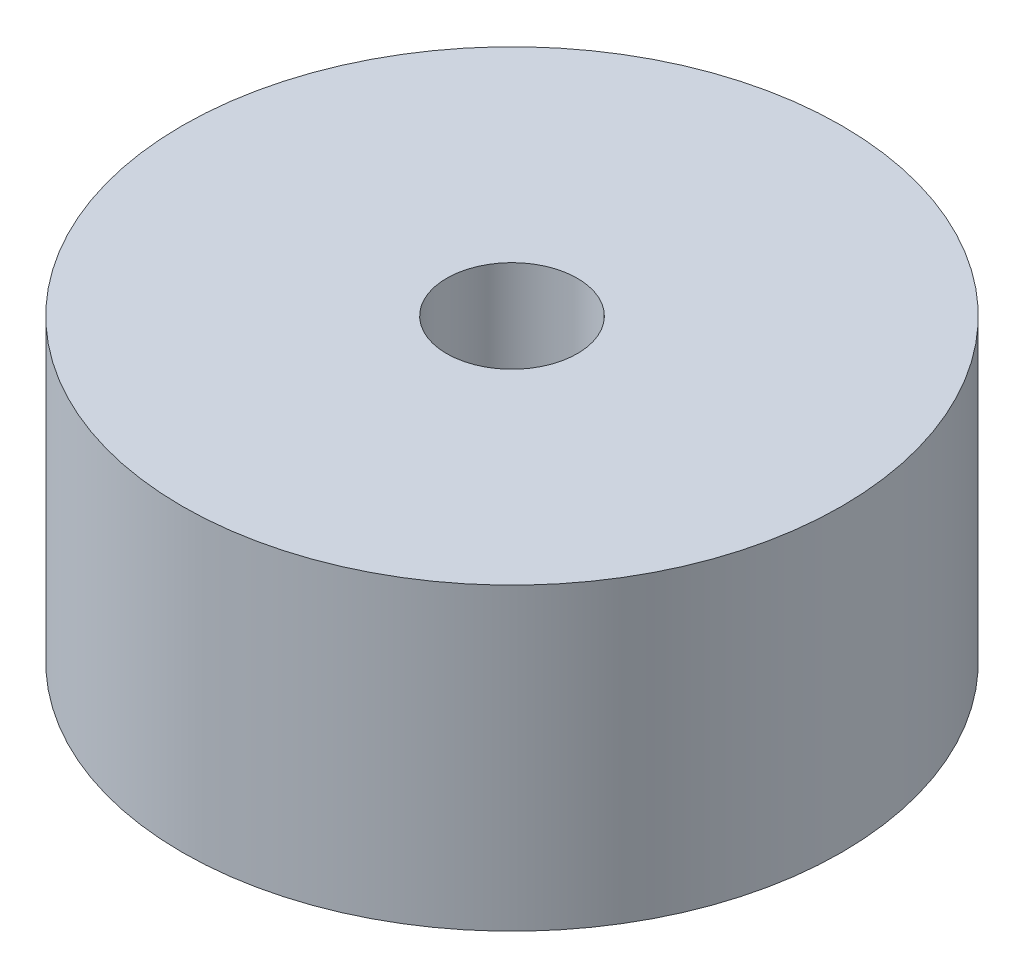
SolidWorks part; units mm, degrees
ref_plane "Front Plane" through (0, 0, 0) normal (0, 0, 1) x (1, 0, 0)
ref_plane "Top Plane" through (0, 0, 0) normal (0, 1, 0) x (1, 0, 0)
ref_plane "Right Plane" through (0, 0, 0) normal (1, 0, 0) x (0, 0, -1)
sketch "Sketch1" plane through (0, 0, 0) normal (0, 1, 0) x (1, 0, 0)
  line L0 (0, 0) -> (99.948, 0) construction
  circle A1 centre (0, 0) radius 1.09
  circle A2 centre (0, 0) radius 5.5
  dimension "D1" = 2.18
  dimension "D2" = 11
extrude "Boss-Extrude1" add sketch "Sketch1" along normal blind 5
